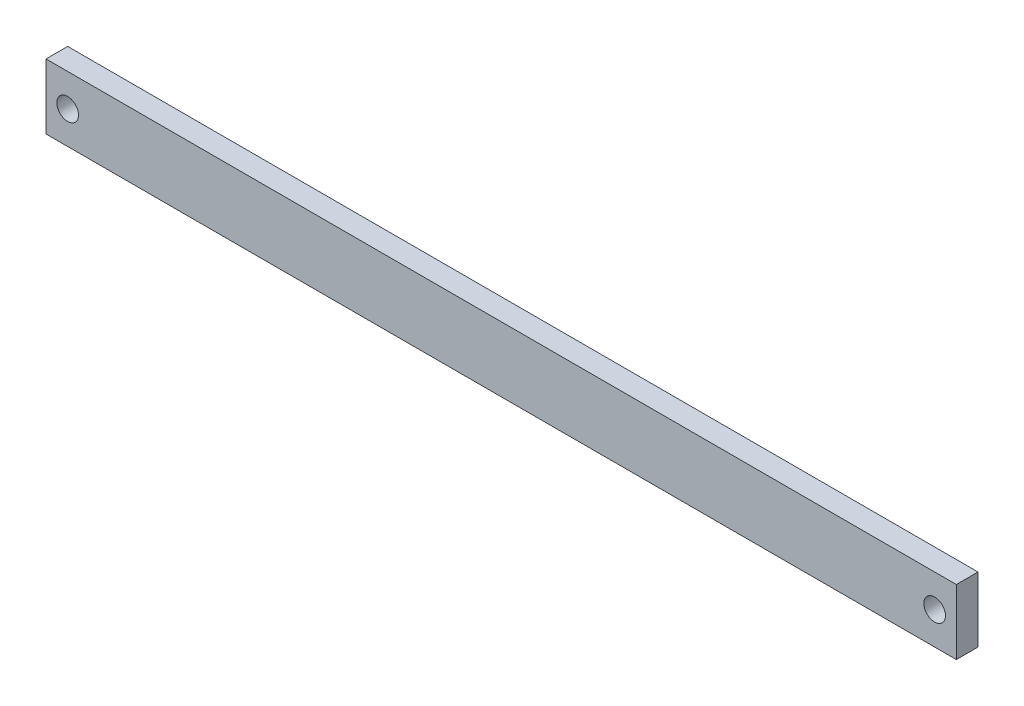
SolidWorks part; units mm, degrees
ref_plane "Front Plane" through (0, 0, 0) normal (0, 0, 1) x (1, 0, 0)
ref_plane "Top Plane" through (0, 0, 0) normal (0, 1, 0) x (1, 0, 0)
ref_plane "Right Plane" through (0, 0, 0) normal (1, 0, 0) x (0, 0, -1)
sketch "Sketch1" plane through (0, 0, 0) normal (0, 0, 1) x (1, 0, 0)
  line L1 (-105, -7.5) -> (105, -7.5)
  line L2 (-105, -7.5) -> (-105, 7.5)
  line L3 (-105, 7.5) -> (105, 7.5)
  line L4 (105, -7.5) -> (105, 7.5)
  line L5 (-105, -7.5) -> (105, 7.5) construction
  line L6 (-105, 7.5) -> (105, -7.5) construction
  circle A0 centre (100, 0) radius 2.5
  circle A1 centre (-100, 0) radius 2.5
  point P0 (0, 0)
  point P10 (0, 0)
  point P11 (-105, 0)
  point P12 (0, 0)
  point P13 (105, 0)
  point P14 (0, 0)
  dimension "D1" = 5
  dimension "D2" = 15
  dimension "D3" = 5
  dimension "D4" = 5
  dimension "D5" = 210
extrude "Boss-Extrude1" add sketch "Sketch1" along normal blind 5
equation "\"D4@Sketch1\"=\"D3@Sketch1\""
